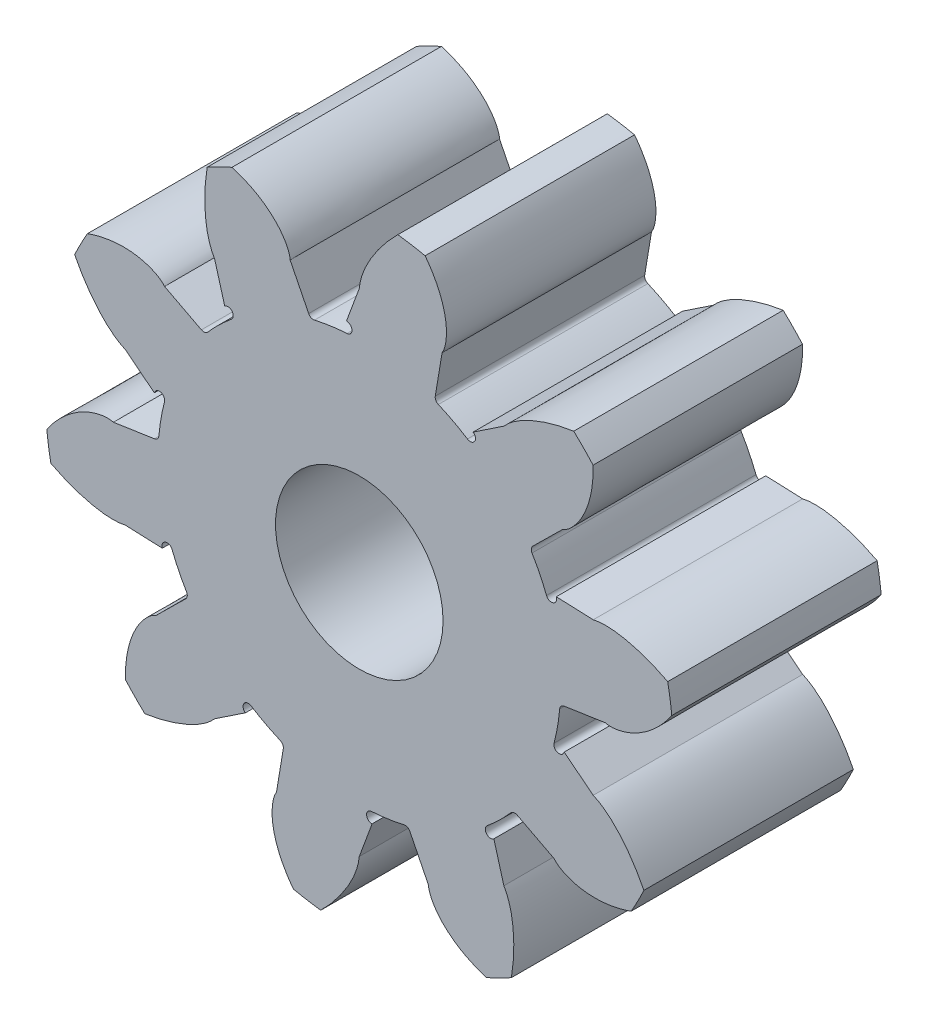
SolidWorks part; units mm, degrees
ref_plane "Alzado" through (0, 0, 0) normal (0, 0, 1) x (1, 0, 0)
ref_plane "Planta" through (0, 0, 0) normal (0, 1, 0) x (1, 0, 0)
ref_plane "Vista lateral" through (0, 0, 0) normal (1, 0, 0) x (0, 0, -1)
sketch "Croquis1" plane through (0, 0, 0) normal (0, 0, 1) x (1, 0, 0)
  line L0 (0, 0) -> (131.0885, 0) construction
  line L1 (0, 0) -> (0, 30) construction
  line L2 (0, 0) -> (4.1529, -4.1529) construction
  line L3 (4.1529, -4.1529) -> (13.9379, 5.6321) construction
  line L4 (0, 0) -> (5.0862, -2.9365) construction
  line L5 (5.0862, -2.9365) -> (11.2365, 7.716) construction
  line L6 (0, 0) -> (5.673, -1.5201) construction
  line L7 (5.673, -1.5201) -> (8.4586, 8.8762) construction
  line L8 (0, 0) -> (5.8731, 0) construction
  line L9 (5.8731, 0) -> (5.8731, 9.2254) construction
  line L10 (0, 0) -> (5.673, 1.5201) construction
  line L11 (5.673, 1.5201) -> (3.6832, 8.946) construction
  line L12 (0, 0) -> (5.0862, 2.9365) construction
  line L13 (5.0862, 2.9365) -> (2.0111, 8.2628) construction
  line L14 (0, 0) -> (4.1529, 4.1529) construction
  line L15 (4.1529, 4.1529) -> (0.8912, 7.4146) construction
  line L16 (0, 0) -> (2.9365, 5.0862) construction
  line L17 (2.9365, 5.0862) -> (0.2734, 6.6238) construction
  line L18 (0, 0) -> (1.5201, 5.673) construction
  line L19 (1.5201, 5.673) -> (0.0349, 6.0709) construction
  circle A0 centre (0, 0) radius 5.8731 construction
  circle A1 centre (0, 0) radius 4.8037 construction
  circle A2 centre (0, 0) radius 7.5 construction
  circle A3 centre (0, 0) radius 6.25 construction
  spline S0 degree 3 poles (0, 5.8731) (0.0268, 6.1412) (0.2749, 6.7039) (0.9499, 7.5456) (2.0946, 8.3898) (3.7913, 9.0646) (6.0084, 9.33) (9.7605, 8.7976) (12.4301, 7.1469) (13.9379, 5.6321) knots 0 0 0 0 0.049397 0.111126 0.197546 0.308655 0.444456 0.604946 1 1 1 1
  point P3 (87.284, 1.25)
  point P4 (102.0506, 10)
  point P5 (119.8936, 20)
  point P29 (0, 5.8731)
  dimension "Diámetro de paso (D)" = 12.5
  dimension "Diámetro de raiz" = 9.6075
  dimension "D1" = 15
  dimension "D2" = 11.7462
  dimension "Módulo (m)" = 1.25
  dimension "Número de dientes (N)" = 10
  dimension "Ángulo de presión (AP)" = 20
  dimension "D3" = 135
  dimension "D4" = 13.8381
  dimension "D5" = 120
  dimension "D6" = 12.3005
  dimension "D7" = 105
  dimension "D8" = 10.763
  dimension "D9" = 9.2254
  dimension "D10" = 90
  dimension "D11" = 75
  dimension "D12" = 7.6878
  dimension "D13" = 60
  dimension "D14" = 6.1503
  dimension "D15" = 45
  dimension "D16" = 4.6127
  dimension "D17" = 30
  dimension "D18" = 3.0751
  dimension "D19" = 15
  dimension "D20" = 1.5376
sketch "Croquis2" plane through (0, 0, 0) normal (0, 0, 1) x (1, 0, 0)
  line L0 (56.3227, 9.5882) -> (76.5884, 9.5882) construction
  line L1 (-0.306, 5.0445) -> (0, 5.8731)
  line L2 (0, 0) -> (0.1893, 13.0101) construction
  line L3 (0, 0) -> (8.4078, 24.6506) construction
  line L4 (0, 0) -> (32.6464, 0) construction
  line L5 (0, 0) -> (131.0885, 0) construction
  line L6 (0, 0) -> (4.3171, 24.9068) construction
  line L7 (1.8141, 4.5525) -> (1.9766, 5.5305)
  line L8 (57.5292, -20.4598) -> (78.7754, -20.4598) construction
  circle A0 centre (0, 0) radius 4.8037 construction
  circle A1 centre (0, 0) radius 7.5 construction
  arc A2 (-0.2916, 4.7949) -> (1.8883, 4.4171) centre (0, 0) ccw
  arc A3 (1.5712, 7.3336) -> (0.9202, 7.4433) centre (0, 0) ccw
  circle A4 centre (0, 0) radius 6.25 construction
  circle A5 centre (0, 0) radius 2
  arc A6 (1.8141, 4.5525) -> (1.8883, 4.4171) centre (1.9374, 4.532) ccw
  arc A7 (-0.306, 5.0445) -> (-0.2916, 4.7949) centre (-0.2992, 4.9197) cw
  spline S0 degree 3 poles (1997.7963, -82.6649) (18.5208, -26.7041) (-4.9998, 0.1256) (0.9499, 7.5456) (2.0946, 8.3898) (3.7913, 9.0646) (6.0084, 9.33) (48.5252, 3.2977) (23.9578, -237.4407) (-1562.5961, 1228.6391) knots -1.543818 -1.543818 -1.543818 -1.543818 0.049397 0.111126 0.197546 0.308655 0.444456 0.604946 8.142519 8.142519 8.142519 8.142519 only from (0, 5.8731) to (13.9379, 5.6321) construction
  spline S1 degree 3 poles (0, 5.8731) (0.0268, 6.1412) (0.2749, 6.7039) (0.6632, 7.1881) (0.9105, 7.4338) (0.9202, 7.4433) knots 0 0 0 0 0.049397 0.111126 0.113633 0.113633 0.113633 0.113633
  spline S2 degree 3 poles (1.9766, 5.5305) (2.0311, 5.6174) (2.0878, 5.8446) (2.0812, 6.2555) (1.9338, 6.7767) (1.7205, 7.1385) (1.576, 7.3274) (1.5712, 7.3336) knots 0 0 0 0 0.049397 0.111126 0.197546 0.308655 0.312445 0.312445 0.312445 0.312445
  point P8 (0.0909, 6.2493)
  point P13 (28.0519, 1.9635)
  point P22 (68.2533, 14.5882)
  point P25 (68.2533, -10.4598)
  dimension "Diámetro del cubo" = 4
  dimension "Redondeo" = 0.125
  dimension "Espesor del diente (T)" = 1.9635
  dimension "D1" = 18
  dimension "D2" = 9
  dimension "Espesor del engrane" = 5
  dimension "dientes" = 10
extrude "Saliente-Extruir1" add sketch "Croquis2" along normal blind 5
pattern_circular "MatrizC6" count 10 over 360 about axis through (0, 0, 5) along (0, 0, -1) of "Saliente-Extruir1"
equation "\"Diámetro de paso (D)@Croquis1\"=\"Módulo (m)@Croquis1\"*\"Número de dientes (N)@Croquis1\""
equation "\"Diámetro de raiz@Croquis1\"=(\"Diámetro de paso (D)@Croquis1\")-((2.314)*(\"Módulo (m)@Croquis1\"))"
equation "\"D1@Croquis1\"=(\"Diámetro de paso (D)@Croquis1\")+((2)*(\"Módulo (m)@Croquis1\"))"
equation "\"D2@Croquis1\"=(\"Diámetro de paso (D)@Croquis1\")*(cos( \"Ángulo de presión (AP)@Croquis1\"))"
equation "\"D4@Croquis1\"=(\"D2@Croquis1\"/(2))*((\"D3@Croquis1\")*(PI)/(180))"
equation "\"D6@Croquis1\"=(\"D2@Croquis1\"/(2))*((\"D5@Croquis1\")*(PI)/(180))"
equation "\"D8@Croquis1\"=(\"D2@Croquis1\"/(2))*((\"D7@Croquis1\")*(PI)/(180))"
equation "\"D9@Croquis1\"=(\"D2@Croquis1\"/(2))*((\"D10@Croquis1\")*(PI)/(180))"
equation "\"D12@Croquis1\"=(\"D2@Croquis1\"/(2))*((\"D11@Croquis1\")*(PI)/(180))"
equation "\"D14@Croquis1\"=(\"D2@Croquis1\"/(2))*((\"D13@Croquis1\")*(PI)/(180))"
equation "\"D16@Croquis1\"=(\"D2@Croquis1\"/(2))*((\"D15@Croquis1\")*(PI)/(180))"
equation "\"D18@Croquis1\"=(\"D2@Croquis1\"/(2))*((\"D17@Croquis1\")*(PI)/(180))"
equation "\"D20@Croquis1\"=(\"D2@Croquis1\"/(2))*((\"D19@Croquis1\")*(PI)/(180))"
equation "\"Espesor del diente (T)@Croquis2\"=(1.5708)*(\"Módulo (m)@Croquis1\")"
equation "\"D1@Croquis2\"=(\"Espesor del diente (T)@Croquis2\"/(\"Diámetro de paso (D)@Croquis1\"/2))*(180/PI)"
equation "\"D2@Croquis2\"= \"D1@Croquis2\" / 2"
equation "\"D1@Saliente-Extruir1\"=\"Espesor del engrane@Croquis2\""
equation "\"dientes@Croquis2\"=\"Número de dientes (N)@Croquis1\""
equation "\"Redondeo@Croquis2\"=\"Módulo (m)@Croquis1\"*(0.1)"
equation "\"D1@MatrizC6\"=\"Número de dientes (N)@Croquis1\""
